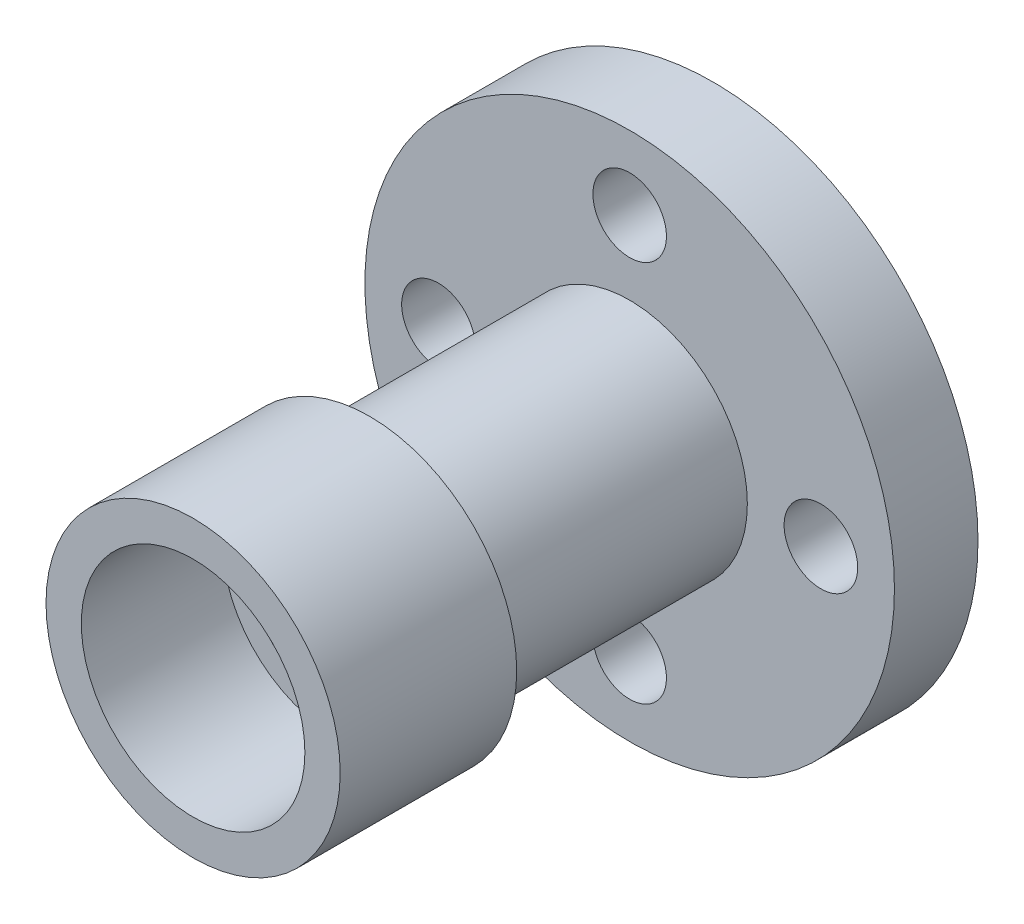
SolidWorks part; units mm, degrees
ref_plane "Alzado" through (0, 0, 0) normal (0, 0, 1) x (1, 0, 0)
ref_plane "Planta" through (0, 0, 0) normal (0, 1, 0) x (1, 0, 0)
ref_plane "Vista lateral" through (0, 0, 0) normal (1, 0, 0) x (0, 0, -1)
sketch "Croquis2" plane through (0, 0, 0) normal (0, 0, 1) x (1, 0, 0)
  circle A0 centre (0, 0) radius 45
  dimension "D1" = 90
extrude "Saliente-Extruir1" add sketch "Croquis2" along normal blind 14.2
sketch "Croquis3" plane through (0, 0, 14.2) normal (0, 0, 1) x (1, 0, 0)
  circle A0 centre (0, 0) radius 20
  dimension "D1" = 40
extrude "Saliente-Extruir2" add sketch "Croquis3" along normal blind 44.2
sketch "Croquis4" plane through (0, 0, 58.4) normal (0, 0, 1) x (1, 0, 0)
  circle A0 centre (0, 0) radius 15
  dimension "D1" = 30
extrude "Cortar-Extruir1" cut sketch "Croquis4" against normal blind 85.2
sketch "Croquis5" plane through (0, 0, 58.4) normal (0, 0, 1) x (1, 0, 0)
  circle A0 centre (0, 0) radius 25
  dimension "D1" = 50
extrude "Saliente-Extruir3" add sketch "Croquis5" along normal blind 30
sketch "Croquis6" plane through (0, 0, 88.4) normal (0, 0, 1) x (1, 0, 0)
  circle A0 centre (0, 0) radius 19
  dimension "D1" = 38
extrude "Cortar-Extruir2" cut sketch "Croquis6" against normal blind 24
sketch "Croquis7" plane through (0, 0, 64.4) normal (0, 0, 1) x (1, 0, 0)
  circle A0 centre (0, 0) radius 15
  dimension "D1" = 30
extrude "Cortar-Extruir3" cut sketch "Croquis7" against normal blind 6
chamfer "Chaflán1" distance 3.5 distance2 3 1 edges at (15, 0, 0)
sketch "Croquis8" plane through (0, 0, 14.2) normal (0, 0, 1) x (1, 0, 0)
  line L0 (0, 0) -> (0, 32.5) construction
  circle A0 centre (0, 32.5) radius 6.25
  circle A1 centre (32.5, 0) radius 6.25
  circle A2 centre (0, -32.5) radius 6.25
  circle A3 centre (-32.5, 0) radius 6.25
  point P13 (0, 0)
  dimension "D2" = 12.5
  dimension "D1" = 32.5
  dimension "D4" = 32.5
  dimension "D5" = 32.5
  dimension "D3" = 4
extrude "Cortar-Extruir4" cut sketch "Croquis8" against normal blind 14.2
